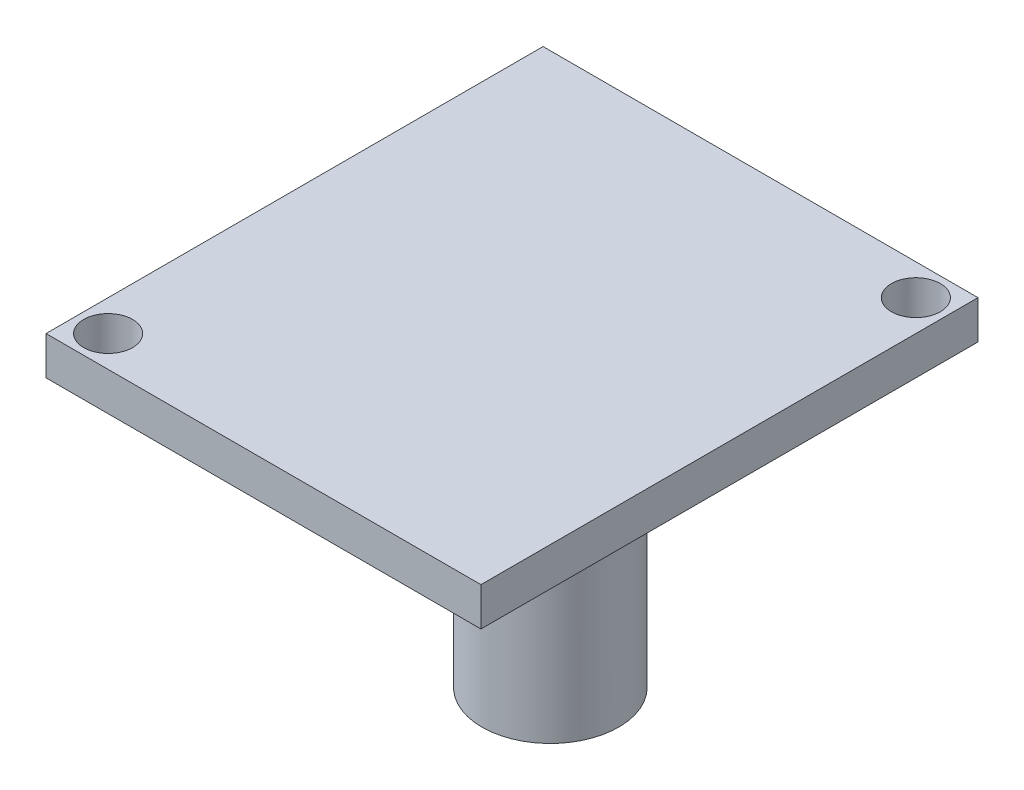
SolidWorks part; units mm, degrees
ref_plane "Front Plane" through (0, 0, 0) normal (0, 0, 1) x (1, 0, 0)
ref_plane "Top Plane" through (0, 0, 0) normal (0, 1, 0) x (1, 0, 0)
ref_plane "Right Plane" through (0, 0, 0) normal (1, 0, 0) x (0, 0, -1)
sketch "Sketch1" plane through (0, 0, 0) normal (0, 1, 0) x (1, 0, 0)
  line L1 (-8.89, -10.16) -> (8.89, -10.16)
  line L2 (-8.89, -10.16) -> (-8.89, 10.16)
  line L3 (-8.89, 10.16) -> (8.89, 10.16)
  line L4 (8.89, -10.16) -> (8.89, 10.16)
  line L5 (-8.89, -10.16) -> (8.89, 10.16) construction
  line L6 (-8.89, 10.16) -> (8.89, -10.16) construction
  point P0 (0, 0)
  dimension "D1" = 17.78
  dimension "D2" = 20.32
extrude "Boss-Extrude1" add sketch "Sketch1" along normal blind 1.57
sketch "Sketch2" plane through (0, 1.57, 0) normal (0, 1, 0) x (1, 0, 0)
  circle A0 centre (5.1554, -3.588) radius 2.7979
  circle A1 centre (-5.0517, 0) radius 2.7979
extrude "Boss-Extrude2" add sketch "Sketch2" against normal blind 8.8
sketch "Sketch3" plane through (0, 1.57, 0) normal (0, 1, 0) x (1, 0, 0)
  line L0 (-8.89, 10.16) -> (-8.89, -10.16) construction
  line L1 (-8.89, -10.16) -> (8.89, -10.16) construction
  line L2 (8.89, 10.16) -> (-8.89, 10.16) construction
  line L3 (8.89, -10.16) -> (8.89, 10.16) construction
  circle A0 centre (-7.62, -8.89) radius 1
  circle A1 centre (7.62, 8.89) radius 1
  point P8 (0, 0)
  point P13 (-7.62, 8.89)
  point P14 (0, 0)
  dimension "D1" = 1.27
  dimension "D2" = 1.27
  dimension "D3" = 1.27
  dimension "D4" = 1.27
  dimension "D5" = 23.4176
  dimension "D6" = 17.78
  dimension "D7" = 15.24
extrude "Cut-Extrude1" cut sketch "Sketch3" against normal through all
